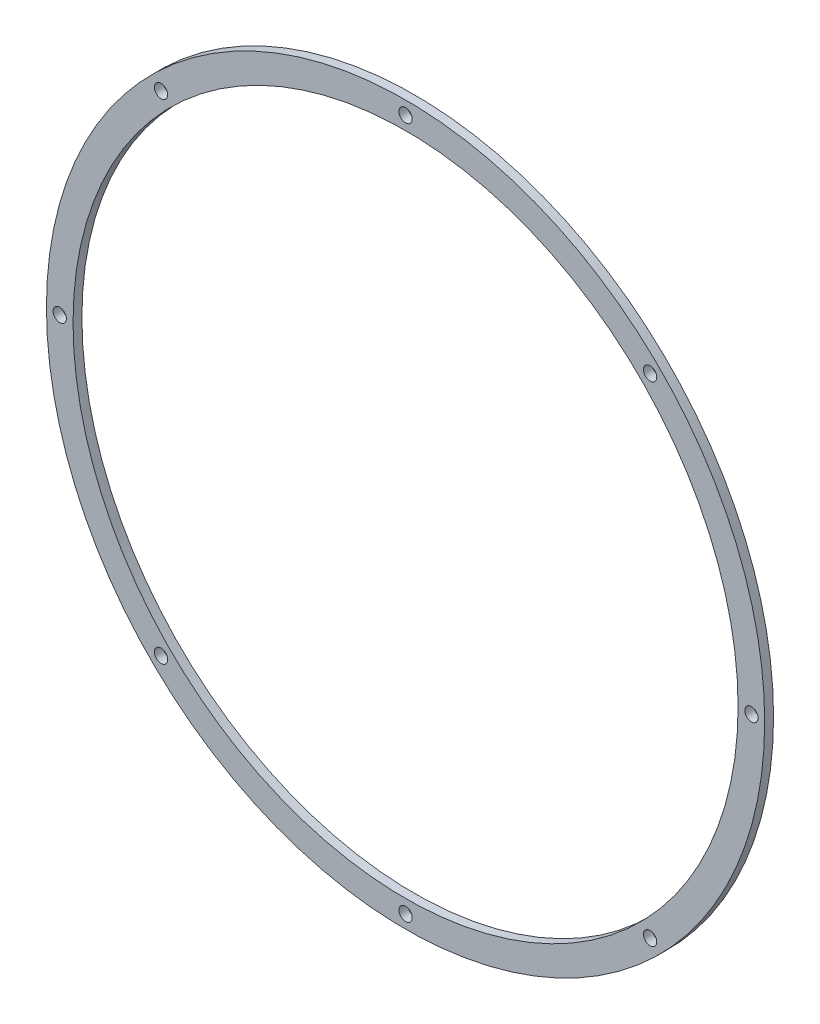
SolidWorks part; units mm, degrees
ref_plane "Płaszczyzna przednia" through (0, 0, 0) normal (0, 0, 1) x (1, 0, 0)
ref_plane "Płaszczyzna górna" through (0, 0, 0) normal (0, 1, 0) x (1, 0, 0)
ref_plane "Płaszczyzna prawa" through (0, 0, 0) normal (1, 0, 0) x (0, 0, -1)
sketch "Szkic1" plane through (0, 0, 0) normal (0, 0, 1) x (1, 0, 0)
  circle A0 centre (0, 0) radius 81
  circle A1 centre (0, 0) radius 75
  dimension "D1" = 162
  dimension "D2" = 150
extrude "Dodanie-wyciągnięcie1" add sketch "Szkic1" along normal blind 2
sketch "Szkic2" plane through (0, 0, 2) normal (0, 0, 1) x (1, 0, 0)
  circle A0 centre (0, 78) radius 1.5
  circle A1 centre (0, 0) radius 75 construction
  circle A2 centre (0, 0) radius 81 construction
  circle A3 centre (0, 0) radius 81 construction
  circle A4 centre (0, 0) radius 75 construction
  dimension "D1" = 3
  dimension "D2" = 162
  dimension "D3" = 78
extrude "Wytnij-wyciągnięcie1" cut sketch "Szkic2" against normal up to surface (2 mm away) up to face at (81, 0, 0)
pattern_circular "Szyk kołowy1" count 8 over 360 about axis through (0, 0, 0) along (0, 0, 1) of "Wytnij-wyciągnięcie1"
equation "\"D3@Szkic2\"=\"D2@Szkic2\"/2-3"
